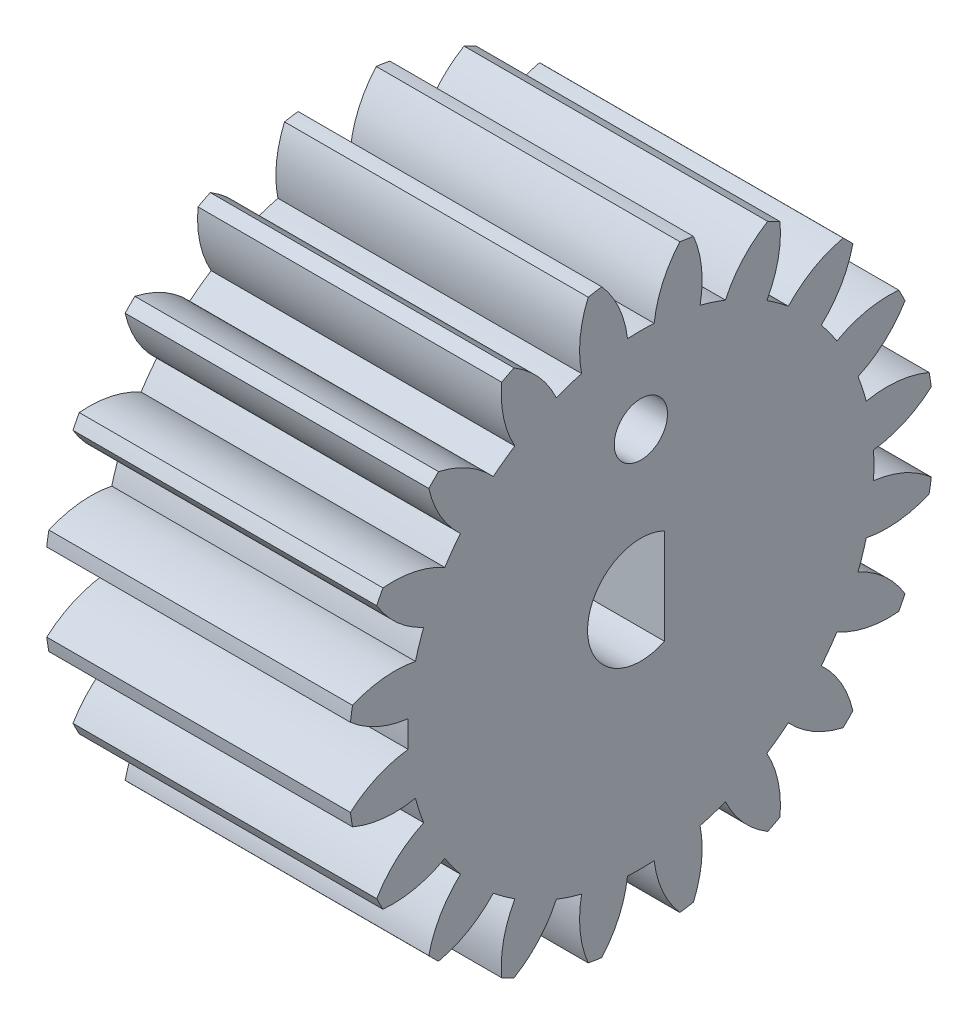
SolidWorks part; units mm, degrees
ref_plane "前视基准面" through (0, 0, 0) normal (0, 0, 1) x (1, 0, 0)
ref_plane "上视基准面" through (0, 0, 0) normal (0, 1, 0) x (1, 0, 0)
ref_plane "右视基准面" through (0, 0, 0) normal (1, 0, 0) x (0, 0, -1)
sketch "草图7" plane through (0, 0, 0) normal (1, 0, 0) x (0, 0, -1)
  line L0 (0.4422, -0.8969) -> (0.4422, 0.8969)
  arc A0 (-5.451, 0.7325) -> (-4.3669, 0.2499) centre (-4.1322, 2.2361) ccw
  arc A1 (-4.3669, 0.2499) -> (-4.3669, -0.2499) centre (0, 0) ccw
  arc A2 (-4.3669, -0.2499) -> (-5.451, -0.7325) centre (-4.1322, -2.2361) ccw
  arc A3 (-5.451, -0.7325) -> (-5.4106, -0.9878) centre (0, 0) ccw
  arc A4 (-5.4106, -0.9878) -> (-4.2304, -1.1118) centre (-4.621, 0.8497) ccw
  arc A5 (-4.2304, -1.1118) -> (-4.0759, -1.5871) centre (0, 0) ccw
  arc A6 (-4.0759, -1.5871) -> (-4.9579, -2.3811) centre (-3.239, -3.4036) ccw
  arc A7 (-4.9579, -2.3811) -> (-4.8405, -2.6114) centre (0, 0) ccw
  arc A8 (-4.8405, -2.6114) -> (-3.6797, -2.3646) centre (-4.6574, -0.6198) ccw
  arc A9 (-3.6797, -2.3646) -> (-3.386, -2.7689) centre (0, 0) ccw
  arc A10 (-3.386, -2.7689) -> (-3.9794, -3.7966) centre (-2.0287, -4.2379) ccw
  arc A11 (-3.9794, -3.7966) -> (-3.7966, -3.9794) centre (0, 0) ccw
  arc A12 (-3.7966, -3.9794) -> (-2.7689, -3.386) centre (-4.2379, -2.0287) ccw
  arc A13 (-2.7689, -3.386) -> (-2.3646, -3.6797) centre (0, 0) ccw
  arc A14 (-2.3646, -3.6797) -> (-2.6114, -4.8405) centre (-0.6198, -4.6574) ccw
  arc A15 (-2.6114, -4.8405) -> (-2.3811, -4.9579) centre (0, 0) ccw
  arc A16 (-2.3811, -4.9579) -> (-1.5871, -4.0759) centre (-3.4036, -3.239) ccw
  arc A17 (-1.5871, -4.0759) -> (-1.1118, -4.2304) centre (0, 0) ccw
  arc A18 (-1.1118, -4.2304) -> (-0.9878, -5.4106) centre (0.8497, -4.621) ccw
  arc A19 (-0.9878, -5.4106) -> (-0.7325, -5.451) centre (0, 0) ccw
  arc A20 (-0.7325, -5.451) -> (-0.2499, -4.3669) centre (-2.2361, -4.1322) ccw
  arc A21 (-0.2499, -4.3669) -> (0.2499, -4.3669) centre (0, 0) ccw
  arc A22 (0.2499, -4.3669) -> (0.7325, -5.451) centre (2.2361, -4.1322) ccw
  arc A23 (0.7325, -5.451) -> (0.9878, -5.4106) centre (0, 0) ccw
  arc A24 (0.9878, -5.4106) -> (1.1118, -4.2304) centre (-0.8497, -4.621) ccw
  arc A25 (1.1118, -4.2304) -> (1.5871, -4.0759) centre (0, 0) ccw
  arc A26 (1.5871, -4.0759) -> (2.3811, -4.9579) centre (3.4036, -3.239) ccw
  arc A27 (2.3811, -4.9579) -> (2.6114, -4.8405) centre (0, 0) ccw
  arc A28 (2.6114, -4.8405) -> (2.3646, -3.6797) centre (0.6198, -4.6574) ccw
  arc A29 (2.3646, -3.6797) -> (2.7689, -3.386) centre (0, 0) ccw
  arc A30 (2.7689, -3.386) -> (3.7966, -3.9794) centre (4.2379, -2.0287) ccw
  arc A31 (3.7966, -3.9794) -> (3.9794, -3.7966) centre (0, 0) ccw
  arc A32 (3.9794, -3.7966) -> (3.386, -2.7689) centre (2.0287, -4.2379) ccw
  arc A33 (3.386, -2.7689) -> (3.6797, -2.3646) centre (0, 0) ccw
  arc A34 (3.6797, -2.3646) -> (4.8405, -2.6114) centre (4.6574, -0.6198) ccw
  arc A35 (4.8405, -2.6114) -> (4.9579, -2.3811) centre (0, 0) ccw
  arc A36 (4.9579, -2.3811) -> (4.0759, -1.5871) centre (3.239, -3.4036) ccw
  arc A37 (4.0759, -1.5871) -> (4.2304, -1.1118) centre (0, 0) ccw
  arc A38 (4.2304, -1.1118) -> (5.4106, -0.9878) centre (4.621, 0.8497) ccw
  arc A39 (5.4106, -0.9878) -> (5.451, -0.7325) centre (0, 0) ccw
  arc A40 (5.451, -0.7325) -> (4.3669, -0.2499) centre (4.1322, -2.2361) ccw
  arc A41 (4.3669, -0.2499) -> (4.3669, 0.2499) centre (0, 0) ccw
  arc A42 (4.3669, 0.2499) -> (5.451, 0.7325) centre (4.1322, 2.2361) ccw
  arc A43 (5.451, 0.7325) -> (5.4106, 0.9878) centre (0, 0) ccw
  arc A44 (5.4106, 0.9878) -> (4.2304, 1.1118) centre (4.621, -0.8497) ccw
  arc A45 (4.2304, 1.1118) -> (4.0759, 1.5871) centre (0, 0) ccw
  arc A46 (4.0759, 1.5871) -> (4.9579, 2.3811) centre (3.239, 3.4036) ccw
  arc A47 (4.9579, 2.3811) -> (4.8405, 2.6114) centre (0, 0) ccw
  arc A48 (4.8405, 2.6114) -> (3.6797, 2.3646) centre (4.6574, 0.6198) ccw
  arc A49 (3.6797, 2.3646) -> (3.386, 2.7689) centre (0, 0) ccw
  arc A50 (3.386, 2.7689) -> (3.9794, 3.7966) centre (2.0287, 4.2379) ccw
  arc A51 (3.9794, 3.7966) -> (3.7966, 3.9794) centre (0, 0) ccw
  arc A52 (3.7966, 3.9794) -> (2.7689, 3.386) centre (4.2379, 2.0287) ccw
  arc A53 (2.7689, 3.386) -> (2.3646, 3.6797) centre (0, 0) ccw
  arc A54 (2.3646, 3.6797) -> (2.6114, 4.8405) centre (0.6198, 4.6574) ccw
  arc A55 (2.6114, 4.8405) -> (2.3811, 4.9579) centre (0, 0) ccw
  arc A56 (2.3811, 4.9579) -> (1.5871, 4.0759) centre (3.4036, 3.239) ccw
  arc A57 (1.5871, 4.0759) -> (1.1118, 4.2304) centre (0, 0) ccw
  arc A58 (1.1118, 4.2304) -> (0.9878, 5.4106) centre (-0.8497, 4.621) ccw
  arc A59 (0.9878, 5.4106) -> (0.7325, 5.451) centre (0, 0) ccw
  arc A60 (0.7325, 5.451) -> (0.2499, 4.3669) centre (2.2361, 4.1322) ccw
  arc A61 (0.2499, 4.3669) -> (-0.2499, 4.3669) centre (0, 0) ccw
  arc A62 (-0.2499, 4.3669) -> (-0.7325, 5.451) centre (-2.2361, 4.1322) ccw
  arc A63 (-0.7325, 5.451) -> (-0.9878, 5.4106) centre (0, 0) ccw
  arc A64 (-0.9878, 5.4106) -> (-1.1118, 4.2304) centre (0.8497, 4.621) ccw
  arc A65 (-1.1118, 4.2304) -> (-1.5871, 4.0759) centre (0, 0) ccw
  arc A66 (-1.5871, 4.0759) -> (-2.3811, 4.9579) centre (-3.4036, 3.239) ccw
  arc A67 (-2.3811, 4.9579) -> (-2.6114, 4.8405) centre (0, 0) ccw
  arc A68 (-2.6114, 4.8405) -> (-2.3646, 3.6797) centre (-0.6198, 4.6574) ccw
  arc A69 (-2.3646, 3.6797) -> (-2.7689, 3.386) centre (0, 0) ccw
  arc A70 (-2.7689, 3.386) -> (-3.7966, 3.9794) centre (-4.2379, 2.0287) ccw
  arc A71 (-3.7966, 3.9794) -> (-3.9794, 3.7966) centre (0, 0) ccw
  arc A72 (-3.9794, 3.7966) -> (-3.386, 2.7689) centre (-2.0287, 4.2379) ccw
  arc A73 (-3.386, 2.7689) -> (-3.6797, 2.3646) centre (0, 0) ccw
  arc A74 (-3.6797, 2.3646) -> (-4.8405, 2.6114) centre (-4.6574, 0.6198) ccw
  arc A75 (-4.8405, 2.6114) -> (-4.9579, 2.3811) centre (0, 0) ccw
  arc A76 (-4.9579, 2.3811) -> (-4.0759, 1.5871) centre (-3.239, 3.4036) ccw
  arc A77 (-4.0759, 1.5871) -> (-4.2304, 1.1118) centre (0, 0) ccw
  arc A78 (-4.2304, 1.1118) -> (-5.4106, 0.9878) centre (-4.621, -0.8497) ccw
  arc A79 (-5.4106, 0.9878) -> (-5.451, 0.7325) centre (0, 0) ccw
  arc A80 (0.4422, 0.8969) -> (0.4422, -0.8969) centre (0, 0) ccw
  circle A81 centre (0, 2.7689) radius 0.5
  dimension "D1" = 4.374
  dimension "D2" = 2
  dimension "D3" = 1
  dimension "D4" = 0.4422
extrude "凸台-拉伸3" add sketch "草图7" along normal blind 5.7
